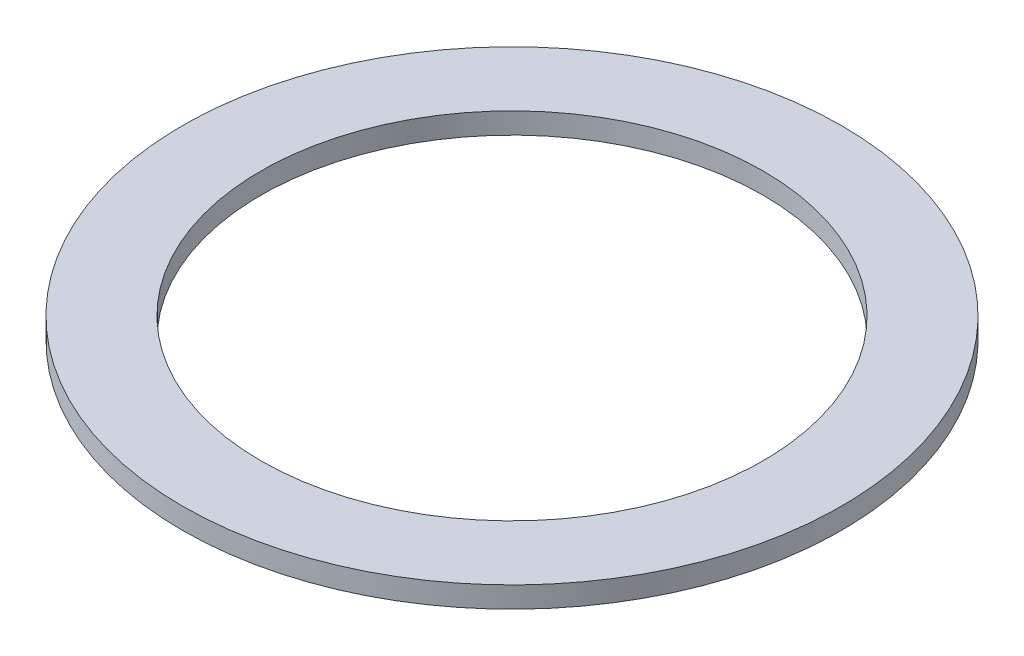
SolidWorks part; units mm, degrees
material "Balsa"
ref_plane "Front Plane" through (0, 0, 0) normal (0, 0, 1) x (1, 0, 0)
ref_plane "Top Plane" through (0, 0, 0) normal (0, 1, 0) x (1, 0, 0)
ref_plane "Right Plane" through (0, 0, 0) normal (1, 0, 0) x (0, 0, -1)
sketch "Sketch1" plane through (0, 0, 0) normal (0, 1, 0) x (1, 0, 0)
  circle A0 centre (0, 0) radius 105
  circle A1 centre (0, 0) radius 80
  dimension "D1" = 105
  dimension "D2" = 80
extrude "Boss-Extrude1" add sketch "Sketch1" along normal blind 6.7 contours A0
equation "\"Ring inner radius\"= 80mm"
equation "\"D1@Sketch1\" = \"Ring outer radius\""
equation "\"Heart cable hole radius\"= 3.5mm"
equation "\"Dogbone radius\"= 3mm"
equation "\"Tree side stock thickness\"= 6.7mm"
equation "\"Ring stock thickness\"= 6.7mm"
equation "\"D1@Boss-Extrude1\"= \"Ring stock thickness\""
equation "\"Tree teeth\"= 15mm"
equation "\"Tree slot\"= 15mm"
equation "\"Bottom ring outer radius\"= \"Ring inner radius\" + \"Tree teeth\""
equation "\"Cut-Extrude Tolerance\"= 5mm"
equation "\"Ring outer radius\"= \"Ring inner radius\" + \"Tree slot\" + 10"
equation "\"D2@Sketch1\"= \"Ring inner radius\""
